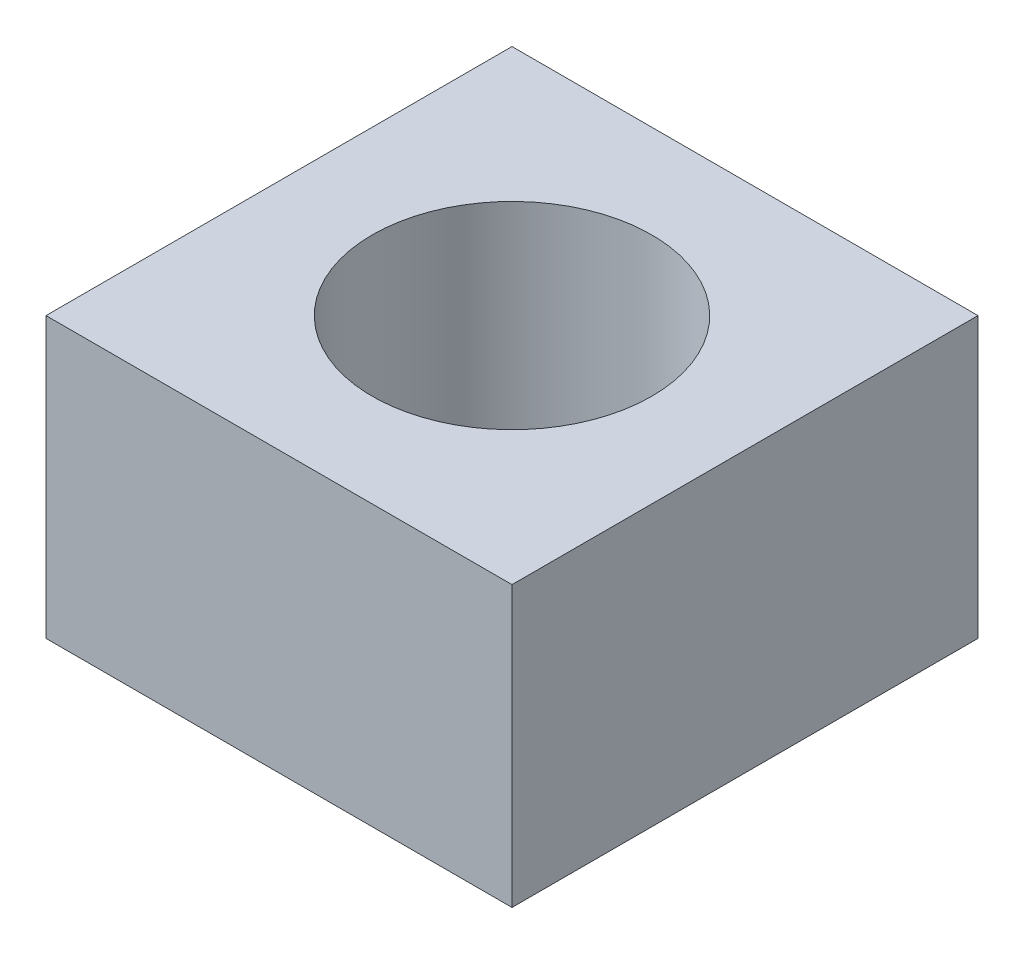
SolidWorks part; units mm, degrees
ref_plane "Front Plane" through (0, 0, 0) normal (0, 0, 1) x (1, 0, 0)
ref_plane "Top Plane" through (0, 0, 0) normal (0, 1, 0) x (1, 0, 0)
ref_plane "Right Plane" through (0, 0, 0) normal (1, 0, 0) x (0, 0, -1)
sketch "Sketch1" plane through (0, 0, 0) normal (0, 0, 1) x (1, 0, 0)
  line L0 (0, 0) -> (5, 0)
  line L1 (5, 0) -> (5, 3)
  line L2 (5, 3) -> (0, 3)
  line L3 (0, 3) -> (0, 0)
  dimension "D1" = 3
  dimension "D2" = 5
  dimension "D3" = 5
extrude "Boss-Extrude1" add sketch "Sketch1" along normal blind 5
sketch "Sketch2" plane through (0, 3, 0) normal (0, 1, 0) x (1, 0, 0)
  line L0 (2.5, 0) -> (2.5, -5) construction
  line L1 (5, 0) -> (0, 0) construction
  line L2 (5, -5) -> (0, -5) construction
  circle A0 centre (2.5, -2.5) radius 1.5
extrude "Cut-Extrude1" cut sketch "Sketch2" against normal through all
